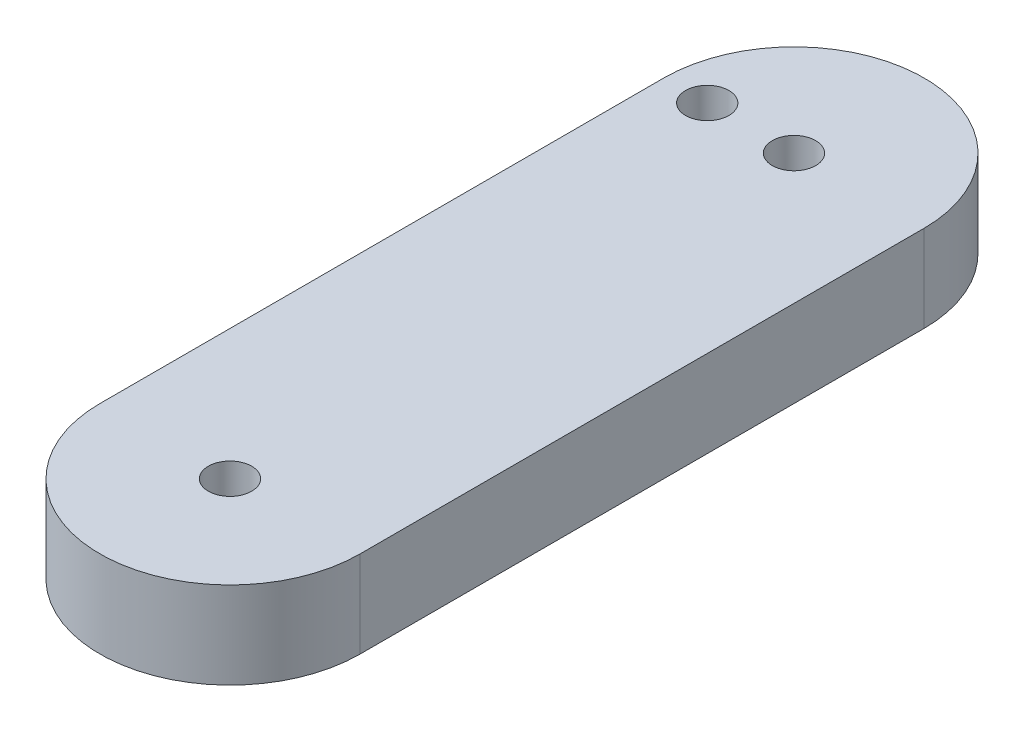
SolidWorks part; units mm, degrees
ref_plane "前视基准面" through (0, 0, 0) normal (0, 0, 1) x (1, 0, 0)
ref_plane "上视基准面" through (0, 0, 0) normal (0, 1, 0) x (1, 0, 0)
ref_plane "右视基准面" through (0, 0, 0) normal (1, 0, 0) x (0, 0, -1)
sketch "草图1" plane through (0, 0, 0) normal (0, 1, 0) x (1, 0, 0)
  line L0 (0, 0) -> (0, 65)
  line L2 (30, 65) -> (30, 0)
  arc A0 (0, 65) -> (30, 65) centre (15, 65) cw
  arc A1 (30, 0) -> (0, 0) centre (15, 0) cw
  dimension "D2" = 15
  dimension "D1" = 65
extrude "凸台-拉伸1" add sketch "草图1" along normal blind 10
sketch "草图2" plane through (0, 10, 0) normal (0, 1, 0) x (1, 0, 0)
  line L0 (15, 80) -> (15, -7.5699) construction
  line L1 (0, 65) -> (22.5459, 65) construction
  line L2 (0, 32.5) -> (37.2689, 32.5) construction
  line L3 (0, 65) -> (0, 0) construction
  arc A0 (30, 65) -> (0, 65) centre (15, 65) ccw construction
  circle A1 centre (15, 65) radius 2.5
  circle A2 centre (15, 0) radius 2.5
  dimension "D1" = 5
extrude "切除-拉伸1" cut sketch "草图2" against normal through all both and the other way through all
sketch "草图4" plane through (0, 10, 0) normal (0, 1, 0) x (1, 0, 0)
  line L0 (15, 65) -> (5, 65) construction
  circle A1 centre (5, 65) radius 2.5
  dimension "D1" = 5
  dimension "D2" = 10
extrude "切除-拉伸3" cut sketch "草图4" against normal blind 10
